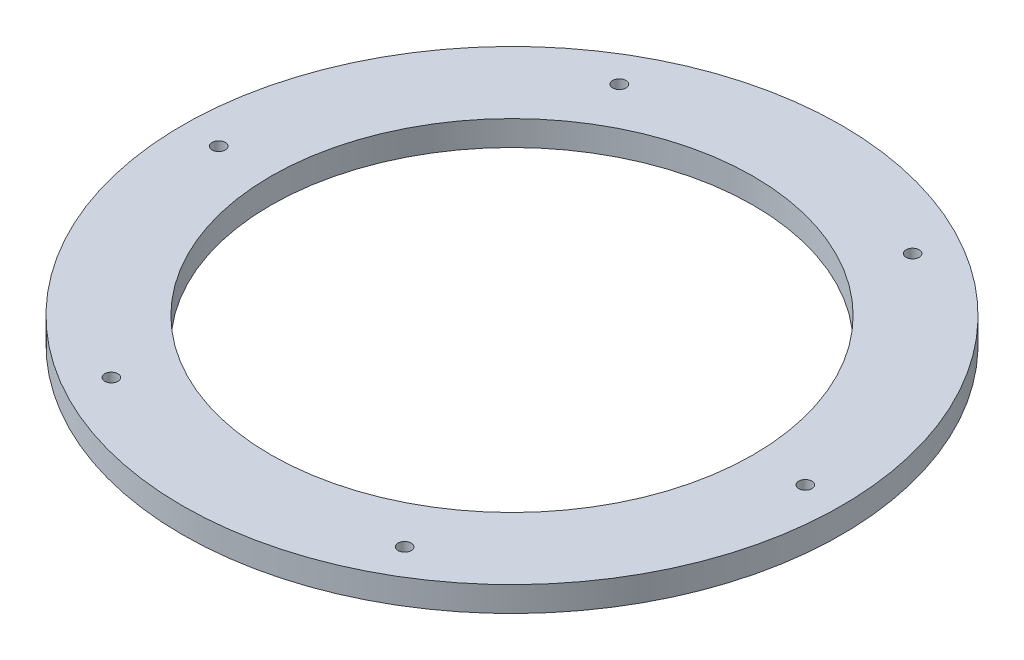
SolidWorks part; units mm, degrees
material "Pine"
ref_plane "Front Plane" through (0, 0, 0) normal (0, 0, 1) x (1, 0, 0)
ref_plane "Top Plane" through (0, 0, 0) normal (0, 1, 0) x (1, 0, 0)
ref_plane "Right Plane" through (0, 0, 0) normal (1, 0, 0) x (0, 0, -1)
sketch "Sketch1" plane through (0, 0, 0) normal (0, 1, 0) x (1, 0, 0)
  circle A1 centre (0, 0) radius 183
  circle A3 centre (0, 0) radius 250
  dimension "D1" = 500
  dimension "D2" = 366
extrude "Boss-Extrude1" add sketch "Sketch1" along normal mid plane 19
sketch "Sketch2" plane through (0, 9.5, 0) normal (0, 1, 0) x (1, 0, 0)
  line L0 (-1000, 0) -> (49000, 0) construction
  line L1 (0, -1000) -> (0, 49000) construction
  line L2 (-500, -866.0254) -> (24500, 42435.2448) construction
  line L3 (-500, 866.0254) -> (24500, -42435.2448) construction
  circle A0 centre (111.25, 192.6907) radius 5
  circle A1 centre (222.5, 0) radius 5
  circle A2 centre (-111.25, 192.6907) radius 5
  circle A3 centre (-222.5, 0) radius 5
  circle A4 centre (111.25, -192.6907) radius 5
  circle A5 centre (-111.25, -192.6907) radius 5
  dimension "D1" = 10
  dimension "D2" = 10
  dimension "D3" = 222.5
  dimension "D4" = 222.5
extrude "Cut-Extrude1" cut sketch "Sketch2" against normal through all
